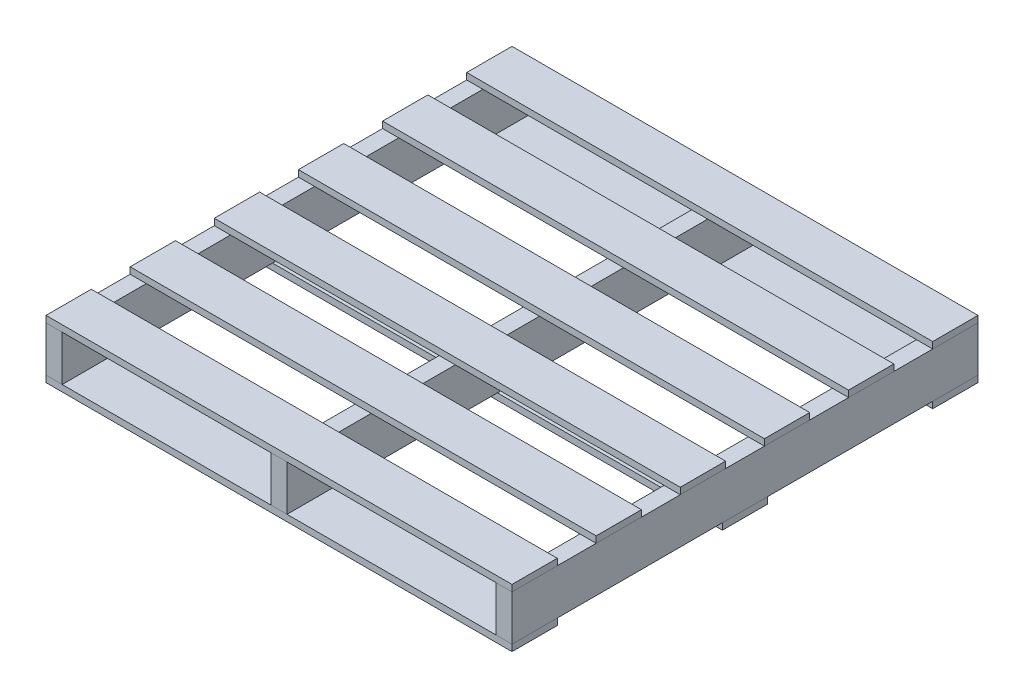
SolidWorks part; units mm, degrees
ref_plane "Front Plane" through (0, 0, 0) normal (0, 0, 1) x (1, 0, 0)
ref_plane "Top Plane" through (0, 0, 0) normal (0, 1, 0) x (1, 0, 0)
ref_plane "Right Plane" through (0, 0, 0) normal (1, 0, 0) x (0, 0, -1)
sketch "Sketch1" plane through (0, 0, 0) normal (0, 0, 1) x (1, 0, 0)
  line L0 (-457.2, 0) -> (457.2, 0) construction
  line L5 (-457.2, 57.15) -> (-457.2, -57.15) construction
  line L6 (457.2, 57.15) -> (457.2, -57.15) construction
  line L11 (-457.2, -57.15) -> (457.2, -57.15) construction
  line L12 (-457.2, 57.15) -> (457.2, 57.15) construction
  line L13 (-425.45, 57.15) -> (-425.45, -57.15) construction
  line L14 (425.45, 57.15) -> (425.45, -57.15) construction
  line L15 (-15.748, 57.15) -> (-15.748, -57.15) construction
  line L16 (15.748, -57.15) -> (15.748, 57.15) construction
  line L17 (0, 57.15) -> (0, -57.15) construction
  line L18 (-457.2, 0) -> (-425.45, 0)
  line L19 (-15.748, 0) -> (0, 0)
  line L20 (0, 0) -> (15.748, 0)
  line L21 (425.45, 0) -> (457.2, 0)
  line L22 (-457.2, 44.45) -> (457.2, 44.45) construction
  line L23 (-457.2, -44.45) -> (457.2, -44.45) construction
  point P3 (0, 0)
  point P6 (-457.2, 0)
  point P9 (457.2, 0)
  point P23 (0, 0)
  dimension "Overall Width" = 914.4
  dimension "Overall Height" = 114.3
  dimension "Maximum Fork Width" = 409.702
  dimension "D2" = 409.702
  dimension "Maximum Fork Height" = 88.9
  dimension "D1" = 31.75
  dimension "D3" = 12.7
sketch "Sketch2" plane through (0, 0, 0) normal (1, 0, 0) x (0, 0, -1)
  line L0 (457.2, 0) -> (-457.2, 0) construction
  point P4 (0, 0)
  dimension "Overall Depth" = 914.4
sketch "Sketch3" plane through (0, 0, 0) normal (0, 0, 1) x (1, 0, 0)
  line L0 (-425.45, 57.15) -> (-425.45, -57.15) construction
  line L1 (-457.2, 44.45) -> (-425.45, 44.45)
  line L2 (-457.2, 44.45) -> (-457.2, -44.45)
  line L3 (-457.2, -44.45) -> (-425.45, -44.45)
  line L4 (-425.45, 44.45) -> (-425.45, -44.45)
  line L5 (-457.2, -44.45) -> (457.2, -44.45) construction
  line L6 (-15.748, 57.15) -> (-15.748, -57.15) construction
  line L7 (-15.748, 44.45) -> (15.748, 44.45)
  line L8 (-15.748, 44.45) -> (-15.748, -44.45)
  line L9 (-15.748, -44.45) -> (15.748, -44.45)
  line L10 (15.748, 44.45) -> (15.748, -44.45)
  line L11 (-457.2, 44.45) -> (457.2, 44.45) construction
  line L12 (15.748, -57.15) -> (15.748, 57.15) construction
  line L13 (425.45, 57.15) -> (425.45, -57.15) construction
  line L14 (425.45, 44.45) -> (457.2, 44.45)
  line L15 (425.45, 44.45) -> (425.45, -44.45)
  line L16 (425.45, -44.45) -> (457.2, -44.45)
  line L17 (457.2, 44.45) -> (457.2, -44.45)
extrude "Boss-Extrude1" add sketch "Sketch3" along normal up to vertex (457.2 mm away) and the other way up to vertex (457.2 mm away) up to point (0, 0, 457.2) other way up to point (0, 0, -457.2)
sketch "Sketch4" plane through (0, 44.45, 0) normal (0, 1, 0) x (1, 0, 0)
  line L0 (457.2, -457.2) -> (457.2, 457.2) construction
  line L1 (-457.2, -457.2) -> (457.2, -457.2)
  line L2 (-457.2, -457.2) -> (-457.2, -368.3)
  line L3 (-457.2, -368.3) -> (457.2, -368.3)
  line L4 (457.2, -457.2) -> (457.2, -368.3)
  line L5 (-457.2, -292.1) -> (457.2, -292.1)
  line L6 (-457.2, -292.1) -> (-457.2, -203.2)
  line L7 (-457.2, -203.2) -> (457.2, -203.2)
  line L8 (457.2, -292.1) -> (457.2, -203.2)
  line L9 (-457.2, -127) -> (457.2, -127)
  line L10 (-457.2, -127) -> (-457.2, -38.1)
  line L11 (-457.2, -38.1) -> (457.2, -38.1)
  line L12 (457.2, -127) -> (457.2, -38.1)
  line L13 (-457.2, 38.1) -> (457.2, 38.1)
  line L14 (-457.2, 38.1) -> (-457.2, 127)
  line L15 (-457.2, 127) -> (457.2, 127)
  line L16 (457.2, 38.1) -> (457.2, 127)
  line L17 (-457.2, 203.2) -> (457.2, 203.2)
  line L18 (-457.2, 203.2) -> (-457.2, 292.1)
  line L19 (-457.2, 292.1) -> (457.2, 292.1)
  line L20 (457.2, 203.2) -> (457.2, 292.1)
  line L21 (-457.2, -457.2) -> (-457.2, 457.2) construction
  line L22 (-457.2, 368.3) -> (457.2, 368.3)
  line L23 (-457.2, 368.3) -> (-457.2, 457.2)
  line L24 (-457.2, 457.2) -> (457.2, 457.2)
  line L25 (457.2, 368.3) -> (457.2, 457.2)
  dimension "D1" = 88.9
  dimension "D3" = 76.2
  dimension "Top Boards" = 6
extrude "Boss-Extrude2" add sketch "Sketch4" along normal up to vertex (12.7 mm away) separate body up to point (-457.2, 57.15, 0)
sketch "Sketch5" plane through (0, -44.45, 0) normal (0, -1, 0) x (1, 0, 0)
  line L0 (457.2, 457.2) -> (457.2, -457.2) construction
  line L1 (-457.2, 457.2) -> (457.2, 457.2)
  line L2 (-457.2, 457.2) -> (-457.2, 368.3)
  line L3 (-457.2, 368.3) -> (457.2, 368.3)
  line L4 (457.2, 457.2) -> (457.2, 368.3)
  line L5 (-457.2, -457.2) -> (457.2, -457.2)
  line L6 (-457.2, -457.2) -> (-457.2, -368.3)
  line L7 (-457.2, -368.3) -> (457.2, -368.3)
  line L8 (457.2, -457.2) -> (457.2, -368.3)
  line L9 (-457.2, -44.45) -> (457.2, -44.45)
  line L10 (-457.2, -44.45) -> (-457.2, 44.45)
  line L11 (-457.2, 44.45) -> (457.2, 44.45)
  line L12 (457.2, -44.45) -> (457.2, 44.45)
  line L13 (-457.2, -44.45) -> (457.2, 44.45) construction
  line L14 (-457.2, 44.45) -> (457.2, -44.45) construction
  line L16 (-457.2, 457.2) -> (-457.2, 368.3) construction
  line L17 (457.2, 457.2) -> (457.2, 368.3) construction
  point P12 (0, 0)
extrude "Boss-Extrude3" add sketch "Sketch5" along normal up to vertex (12.7 mm away) separate body up to point (-457.2, -57.15, 0)
sketch "Sketch7" plane through (0, 0, 0) normal (0, 1, 0) x (1, 0, 0)
  line L0 (0, 457.2) -> (457.2, 457.2) construction
  line L2 (457.2, 457.2) -> (457.2, 0) construction
  line L3 (457.2, 0) -> (457.2, -457.2) construction
  line L4 (457.2, -457.2) -> (0, -457.2) construction
  line L5 (-457.2, -457.2) -> (457.2, -457.2) construction
  line L6 (-457.2, 457.2) -> (0, 457.2) construction
equation "\"D2@Sketch1\" = \"Maximum Fork Width@Sketch1\""
equation "\"D3@Sketch4\" =  ( \"Overall Depth@Sketch2\" -  ( 3.5 * \"Top Boards@Sketch4\" )  )  /  ( \"Top Boards@Sketch4\" - 1 ) "
